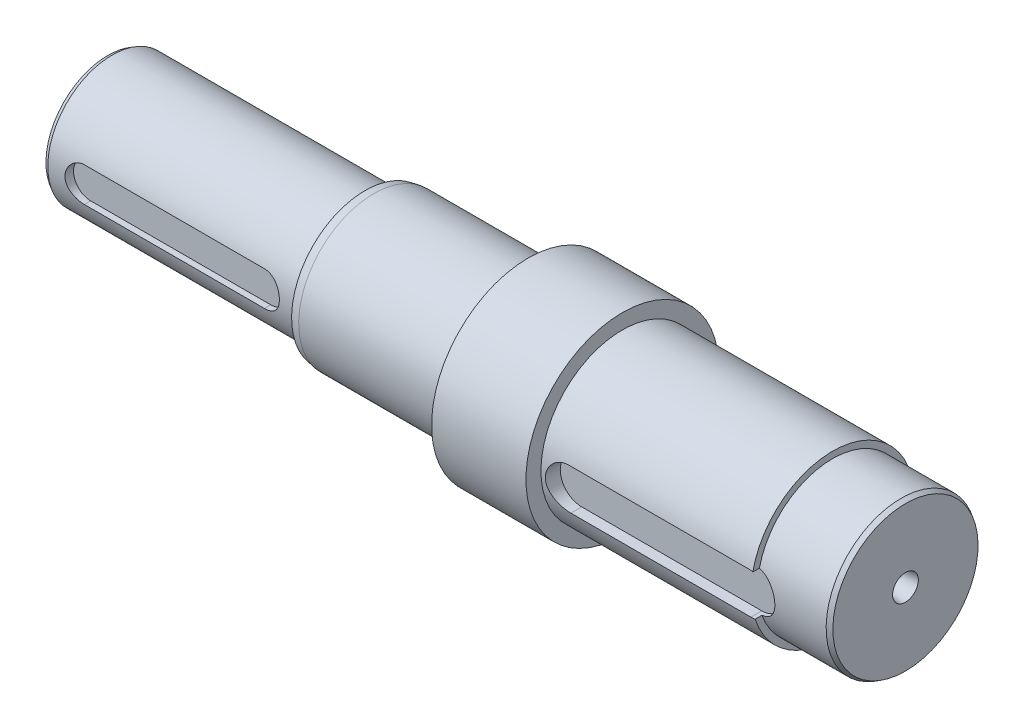
SolidWorks part; units mm, degrees
ref_plane "Front Plane" through (0, 0, 0) normal (0, 0, 1) x (1, 0, 0)
ref_plane "Top Plane" through (0, 0, 0) normal (0, 1, 0) x (1, 0, 0)
ref_plane "Right Plane" through (0, 0, 0) normal (1, 0, 0) x (0, 0, -1)
sketch "Sketch1" plane through (0, 0, 0) normal (0, 0, 1) x (1, 0, 0)
  line L0 (-98.6947, 0) -> (87.3053, 0)
  line L1 (-98.6947, 0) -> (-98.6947, 14.4226)
  line L2 (-97.6947, 15) -> (-38.6947, 15)
  line L3 (-38.6947, 15) -> (-38.6947, 17.1473)
  line L4 (-36.6947, 17.5) -> (-0.6947, 17.5)
  line L5 (-0.6947, 17.5) -> (-0.6947, 22.5)
  line L6 (-0.6947, 22.5) -> (21.3053, 22.5)
  line L7 (21.3053, 22.5) -> (21.3053, 19)
  line L8 (21.3053, 19) -> (70.3053, 19)
  line L9 (70.3053, 19) -> (70.3053, 17.5)
  line L10 (70.3053, 17.5) -> (86.3053, 17.5)
  line L11 (87.3053, 16.9226) -> (87.3053, 0)
  line L13 (86.3053, 17.5) -> (87.3053, 16.9226)
  line L14 (-97.6947, 15) -> (-98.6947, 14.4226)
  line L15 (-36.6947, 17.5) -> (-38.6947, 17.1473)
  point P1 (-0.6947, 20)
  dimension "D1" = 186
  dimension "D2" = 98
  dimension "D4" = 60
  dimension "D5" = 22.5
  dimension "D6" = 17.5
  dimension "D7" = 19
  dimension "D8" = 17.5
  dimension "D9" = 15
  dimension "D10" = 30
  dimension "D11" = 30
  dimension "D12" = 10
revolve "Revolve1" add sketch "Sketch1" angle 360 about L0
sketch "Sketch2" plane through (0, 0, 0) normal (0, 0, 1) x (1, 0, 0)
  line L2 (-89.695, 0.05) -> (-47.695, 0.05) construction
  line L3 (-89.695, 4.05) -> (-47.695, 4.05)
  line L4 (-89.695, -3.95) -> (-47.695, -3.95)
  arc A0 (-89.695, 4.05) -> (-89.695, -3.95) centre (-89.695, 0.05) ccw
  arc A1 (-47.695, -3.95) -> (-47.695, 4.05) centre (-47.695, 0.05) ccw
  point P0 (-93.695, 0.05)
  point P1 (-43.695, 0.05)
  point P7 (-68.695, 0.05)
  dimension "D3" = 8
  dimension "D1" = 5
  dimension "D2" = 50
extrude "Cut-Extrude1" cut sketch "Sketch2" against normal blind 2 from offset 15
sketch "Sketch3" plane through (0, 0, 0) normal (0, 0, 1) x (1, 0, 0)
  line L0 (87.3053, -16.9226) -> (87.3053, 16.9226) construction
  line L7 (27.3053, 4) -> (69.3053, 4)
  line L8 (69.3053, -6) -> (27.3053, -6)
  arc A0 (27.3053, 4) -> (27.3053, -6) centre (27.3053, -1) ccw
  arc A1 (69.3053, -6) -> (69.3053, 4) centre (69.3053, -1) ccw
  point P1 (22.3053, -1)
  point P2 (74.3053, -1)
  dimension "D1" = 10
  dimension "D2" = 52
  dimension "D3" = 13
extrude "Cut-Extrude2" cut sketch "Sketch3" along normal blind 25 from offset 15.5
sketch "Sketch5" plane through (-98.6947, 0, 0) normal (-1, 0, 0) x (0, 0, 1)
  circle A0 centre (0, 0) radius 3
  dimension "D1" = 6
extrude "Cut-Extrude3" cut sketch "Sketch5" against normal blind 31
cosmetic thread "Cosmetic Thread3" parameters "D1"=20, "D2"=7
sketch "Sketch9" plane through (87.3053, 0, 0) normal (1, 0, 0) x (0, 0, -1)
  circle A0 centre (0, 0) radius 3
  dimension "D1" = 6
extrude "Cut-Extrude4" cut sketch "Sketch9" against normal blind 6 draft 8
